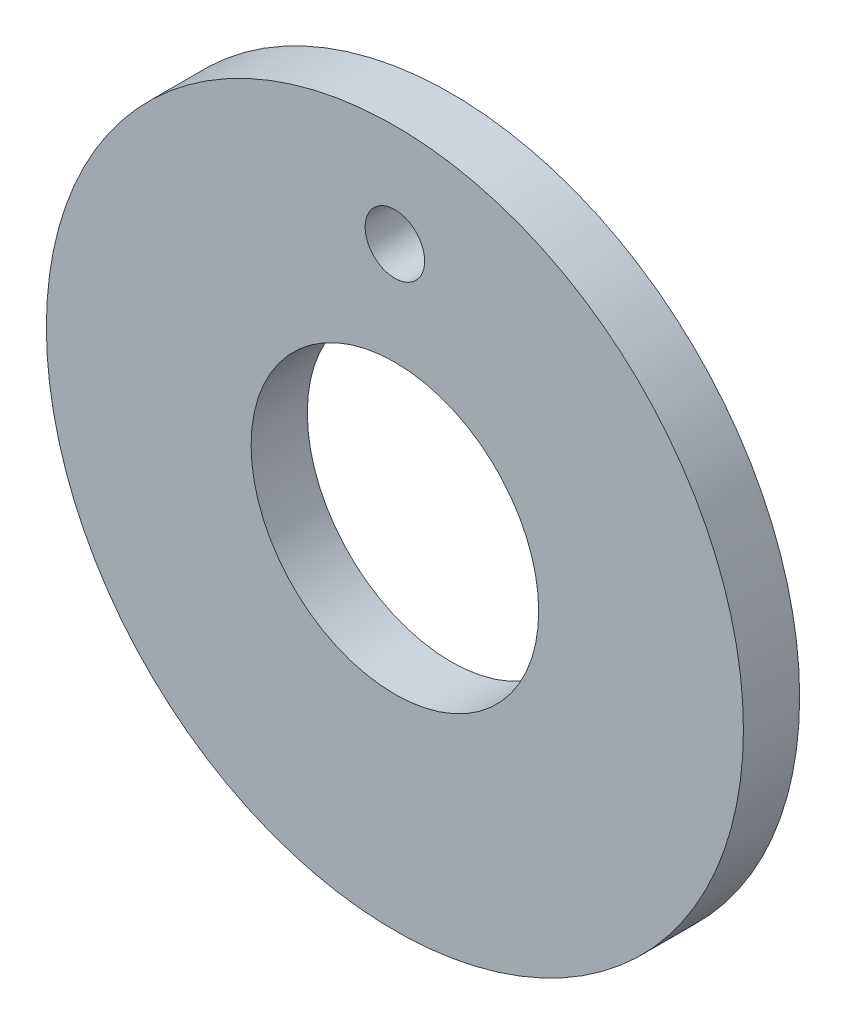
SolidWorks part; units mm, degrees
ref_plane "Front Plane" through (0, 0, 0) normal (0, 0, 1) x (1, 0, 0)
ref_plane "Top Plane" through (0, 0, 0) normal (0, 1, 0) x (1, 0, 0)
ref_plane "Right Plane" through (0, 0, 0) normal (1, 0, 0) x (0, 0, -1)
sketch "Sketch1" plane through (0, 0, 0) normal (0, 0, 1) x (1, 0, 0)
  circle A0 centre (0, 0) radius 15.35
  circle A1 centre (0, 0) radius 37.2
  dimension "D1" = 74.4
  dimension "D2" = 30.7
extrude "Boss-Extrude1" add sketch "Sketch1" along normal blind 6
sketch "Sketch2" plane through (0, 0, 6) normal (0, 0, 1) x (1, 0, 0)
  line L0 (0, 15.35) -> (0, 37.2) construction
  circle A0 centre (0, 26.275) radius 3.175
  circle A1 centre (0, 0) radius 15.35 construction
  circle A2 centre (0, 0) radius 37.2 construction
  point P10 (0, 26.275)
  dimension "D1" = 6.35
extrude "Cut-Extrude1" cut sketch "Sketch2" against normal blind 6
